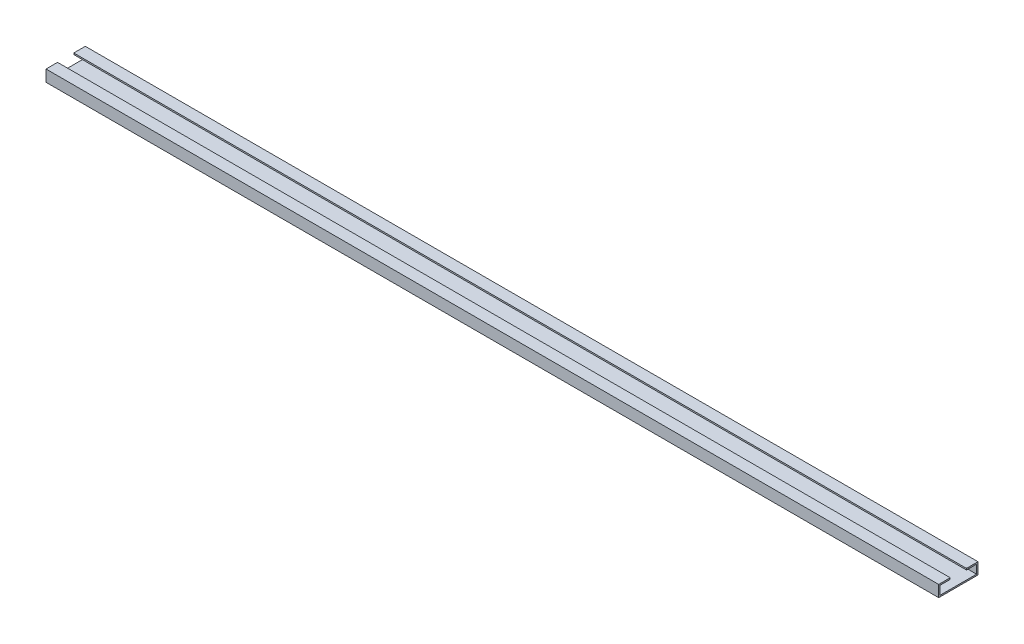
SolidWorks part; units mm, degrees
ref_plane "Ön Düzlem" through (0, 0, 0) normal (0, 0, 1) x (1, 0, 0)
ref_plane "Üst Düzlem" through (0, 0, 0) normal (0, 1, 0) x (1, 0, 0)
ref_plane "Sağ Düzlem" through (0, 0, 0) normal (1, 0, 0) x (0, 0, -1)
ref_plane "Düzlem1" through (0, 0, 0) normal (-1, 0, 0) x (0, -1, 0)
sketch "Çizim1" plane through (0, 0, 0) normal (-1, 0, 0) x (0, -1, 0)
  line L0 (0, 0) -> (-4, 0)
  line L1 (-4, 0) -> (-4, -4)
  line L2 (-4, -4) -> (-3.5, -4)
  line L3 (-3.5, -4) -> (-3.5, -0.5)
  line L4 (-3.5, -0.5) -> (-0.5, -0.5)
  line L5 (-0.5, -0.5) -> (-0.5, -13.15)
  line L6 (-0.5, -13.15) -> (-3.5, -13.15)
  line L7 (-3.5, -13.15) -> (-3.5, -9.65)
  line L8 (-3.5, -9.65) -> (-4, -9.65)
  line L9 (-4, -9.65) -> (-4, -13.65)
  line L10 (-4, -13.65) -> (0, -13.65)
  line L11 (0, -13.65) -> (0, 0)
extrude "Yükseklik-Ekstrüzyon1" add sketch "Çizim1" against normal blind 310
